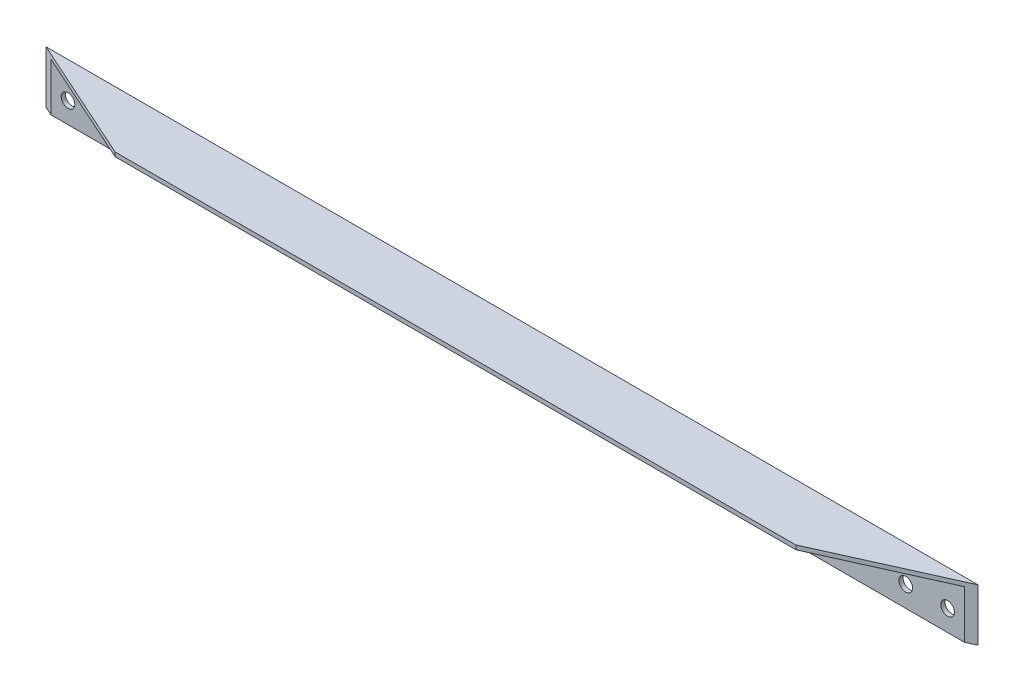
SolidWorks part; units mm, degrees
ref_plane "前视" through (0, 0, 0) normal (0, 0, 1) x (1, 0, 0)
ref_plane "上视" through (0, 0, 0) normal (0, 1, 0) x (1, 0, 0)
ref_plane "右视" through (0, 0, 0) normal (1, 0, 0) x (0, 0, -1)
sketch "草图1" plane through (0, 0, 0) normal (0, 0, 1) x (1, 0, 0)
  line L0 (0, 0) -> (0, 100) construction
  line L1 (-890, 0) -> (890, 0)
  line L2 (-890, 0) -> (-890, 100)
  line L3 (-890, 100) -> (890, 100)
  line L4 (890, 0) -> (890, 100)
  line L5 (1568.3745, 40) -> (890, 40) construction
  line L6 (890, 40) -> (0, 40) construction
  line L7 (468.717, 40) -> (338.4799, 40) construction
  line L8 (890, 40) -> (0, 40) construction
  line L9 (0, 72.6209) -> (0, 232.7989) construction
  line L10 (1000, 433.3131) -> (1000, -1026.6948) construction
  line L11 (-1000, 516.3236) -> (-1000, -1344.0878) construction
  circle A0 centre (840, 40) radius 13
  circle A1 centre (760, 40) radius 13
  circle A7 centre (-840, 40) radius 13
  circle A8 centre (-760, 40) radius 13
  dimension "D4" = 26
  dimension "D5" = 26
  dimension "D8" = 160
  dimension "D1" = 1780
  dimension "D2" = 100
  dimension "D3" = 40
  dimension "D6" = 50
  dimension "D7" = 80
  dimension "D9" = 160
extrude "基体-拉伸" add sketch "草图1" along normal blind 8
sketch "草图2" plane through (0, 0, 8) normal (0, 0, 1) x (1, 0, 0)
  line L0 (890, 0) -> (890, 100) construction
  line L1 (-890, 100) -> (890, 100)
  line L2 (-890, 100) -> (-890, 92)
  line L3 (-890, 92) -> (890, 92)
  line L4 (890, 100) -> (890, 92)
  dimension "D1" = 8
extrude "凸台-拉伸1" add sketch "草图2" along normal blind 100
sketch "草图3" plane through (0, 100, 0) normal (0, 1, 0) x (-1, 0, 0)
  line L0 (-890, 108) -> (890, 108) construction
  line L1 (-650, 108) -> (-890, 0)
  line L2 (-890, 0) -> (-890, 108)
  line L3 (-890, 108) -> (-650, 108)
  line L4 (0, -34.4051) -> (0, 171.3565) construction
  line L5 (890, 108) -> (650, 108)
  line L6 (890, 0) -> (890, 108)
  line L7 (650, 108) -> (890, 0)
  point P0 (-650, 108)
  dimension "D1" = 240
extrude "切除-拉伸1" cut sketch "草图3" against normal through all
